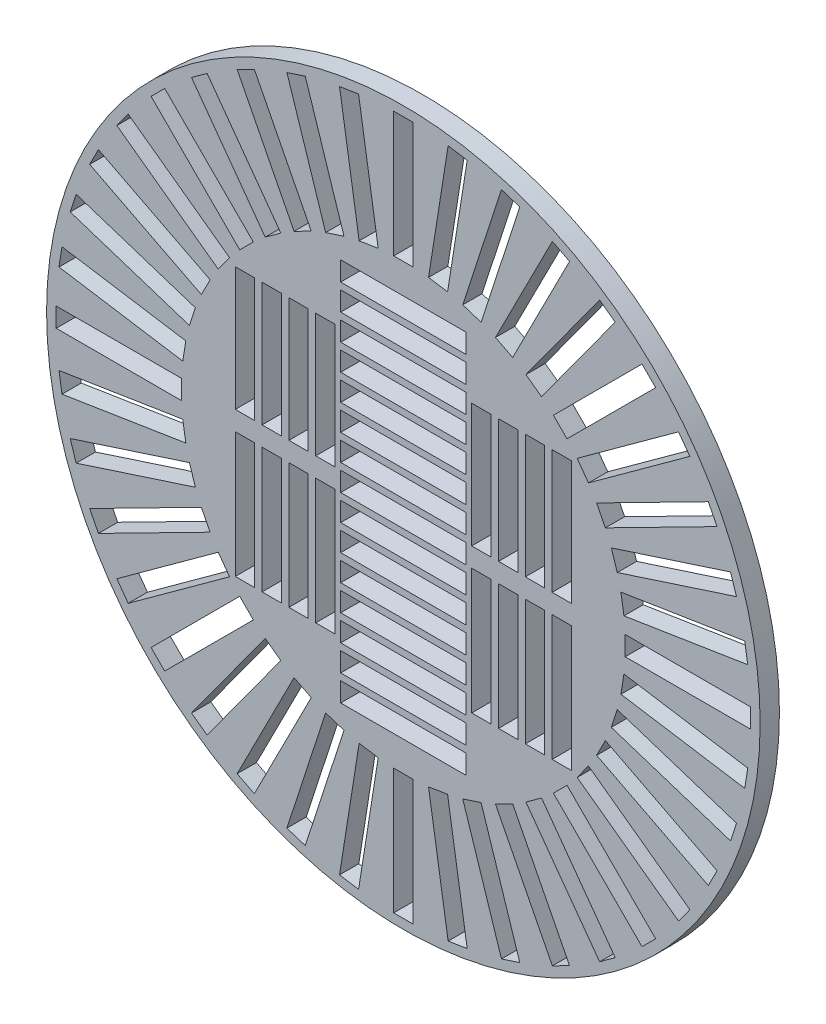
SolidWorks part; units mm, degrees
ref_plane "Front Plane" through (0, 0, 0) normal (0, 0, 1) x (1, 0, 0)
ref_plane "Top Plane" through (0, 0, 0) normal (0, 1, 0) x (1, 0, 0)
ref_plane "Right Plane" through (0, 0, 0) normal (1, 0, 0) x (0, 0, -1)
sketch "Sketch1" plane through (0, 0, 0) normal (0, 0, 1) x (1, 0, 0)
  circle A0 centre (0, 0) radius 37
  point P3 (0, 0)
  point P4 (0, 0)
  point P30 (0, 0)
  dimension "D1" = 74
extrude "Base" add sketch "Sketch1" along normal mid plane 2
sketch "Sketch Ytre ring" plane through (0, 0, 1) normal (0, 0, 1) x (1, 0, 0)
  line L0 (0, 36) -> (0, 37) construction
  line L1 (-1, 36) -> (1, 36)
  line L2 (-1, 36) -> (-1, 23)
  line L3 (-1, 23) -> (1, 23)
  line L4 (1, 36) -> (1, 23)
  circle A0 centre (0, 0) radius 37 construction
  point P4 (0, 23)
  dimension "D1" = 2
  dimension "D3" = 13
  dimension "D2" = 1
extrude "Ytre ring" cut sketch "Sketch Ytre ring" against normal blind 2
pattern_circular "CirPattern1" count 40 over 360 about axis through (0, 0, 0) along (0, 0, 1) of "Ytre ring"
sketch "Sketch3" plane through (0, 0, 1) normal (0, 0, 1) x (1, 0, 0)
  line L0 (-6.5, 3.7) -> (-6.5, 1.7)
  line L5 (-6.5, 1) -> (6.5, 1)
  line L6 (-6.5, 1) -> (-6.5, -1)
  line L7 (-6.5, -1) -> (6.5, -1)
  line L8 (6.5, 1) -> (6.5, -1)
  line L9 (-6.5, 1) -> (6.5, -1) construction
  line L10 (-6.5, -1) -> (6.5, 1) construction
  line L11 (-6.5, 3.7) -> (6.5, 3.7)
  line L12 (6.5, 3.7) -> (6.5, 1.7)
  line L13 (-6.5, 1.7) -> (6.5, 1.7)
  line L14 (-6.5, 6.4) -> (-6.5, 4.4)
  line L15 (-6.5, 6.4) -> (6.5, 6.4)
  line L16 (6.5, 6.4) -> (6.5, 4.4)
  line L17 (-6.5, 4.4) -> (6.5, 4.4)
  line L18 (-6.5, 9.1) -> (-6.5, 7.1)
  line L19 (-6.5, 9.1) -> (6.5, 9.1)
  line L20 (6.5, 9.1) -> (6.5, 7.1)
  line L21 (-6.5, 7.1) -> (6.5, 7.1)
  line L22 (-6.5, 11.8) -> (-6.5, 9.8)
  line L23 (-6.5, 11.8) -> (6.5, 11.8)
  line L24 (6.5, 11.8) -> (6.5, 9.8)
  line L25 (-6.5, 9.8) -> (6.5, 9.8)
  line L26 (-6.5, 14.5) -> (-6.5, 12.5)
  line L27 (-6.5, 14.5) -> (6.5, 14.5)
  line L28 (6.5, 14.5) -> (6.5, 12.5)
  line L29 (-6.5, 12.5) -> (6.5, 12.5)
  line L30 (-6.5, 17.2) -> (-6.5, 15.2)
  line L31 (-6.5, 17.2) -> (6.5, 17.2)
  line L32 (6.5, 17.2) -> (6.5, 15.2)
  line L33 (-6.5, 15.2) -> (6.5, 15.2)
  line L34 (-6.5, 19.9) -> (-6.5, 17.9)
  line L35 (-6.5, 19.9) -> (6.5, 19.9)
  line L36 (6.5, 19.9) -> (6.5, 17.9)
  line L37 (-6.5, 17.9) -> (6.5, 17.9)
  line L38 (-6.5, -1.7) -> (-6.5, -3.7)
  line L39 (-6.5, -1.7) -> (6.5, -1.7)
  line L40 (6.5, -1.7) -> (6.5, -3.7)
  line L41 (-6.5, -3.7) -> (6.5, -3.7)
  line L42 (-6.5, -4.4) -> (-6.5, -6.4)
  line L43 (-6.5, -4.4) -> (6.5, -4.4)
  line L44 (6.5, -4.4) -> (6.5, -6.4)
  line L45 (-6.5, -6.4) -> (6.5, -6.4)
  line L46 (-6.5, -7.1) -> (-6.5, -9.1)
  line L47 (-6.5, -7.1) -> (6.5, -7.1)
  line L48 (6.5, -7.1) -> (6.5, -9.1)
  line L49 (-6.5, -9.1) -> (6.5, -9.1)
  line L50 (-6.5, -9.8) -> (-6.5, -11.8)
  line L51 (-6.5, -9.8) -> (6.5, -9.8)
  line L52 (6.5, -9.8) -> (6.5, -11.8)
  line L53 (-6.5, -11.8) -> (6.5, -11.8)
  line L54 (-6.5, -12.5) -> (-6.5, -14.5)
  line L55 (-6.5, -12.5) -> (6.5, -12.5)
  line L56 (6.5, -12.5) -> (6.5, -14.5)
  line L57 (-6.5, -14.5) -> (6.5, -14.5)
  line L58 (-6.5, -15.2) -> (-6.5, -17.2)
  line L59 (-6.5, -15.2) -> (6.5, -15.2)
  line L60 (6.5, -15.2) -> (6.5, -17.2)
  line L61 (-6.5, -17.2) -> (6.5, -17.2)
  line L62 (-6.5, -17.9) -> (-6.5, -19.9)
  line L63 (-6.5, -17.9) -> (6.5, -17.9)
  line L64 (6.5, -17.9) -> (6.5, -19.9)
  line L65 (-6.5, -19.9) -> (6.5, -19.9)
  line L66 (0, 0) -> (0, 2.8459) construction
  line L67 (0, 0) -> (3.4244, 0) construction
  line L68 (-8.089, 1) -> (-8.089, -1) construction
  line L69 (-9.089, 13.8166) -> (-7.089, 13.8166)
  line L70 (-9.089, 13.8166) -> (-9.089, 1)
  line L71 (-9.089, 1) -> (-7.089, 1)
  line L72 (-7.089, 13.8166) -> (-7.089, 1)
  line L73 (-9.089, 13.8166) -> (-7.089, 1) construction
  line L74 (-9.089, 1) -> (-7.089, 13.8166) construction
  line L75 (-9.089, -1) -> (-7.089, -1)
  line L76 (-9.089, -1) -> (-9.089, -14)
  line L77 (-9.089, -14) -> (-7.089, -14)
  line L78 (-7.089, -1) -> (-7.089, -14)
  line L79 (-9.089, -1) -> (-7.089, -14) construction
  line L80 (-9.089, -14) -> (-7.089, -1) construction
  line L81 (-11.869, 13.8166) -> (-11.869, 1)
  line L82 (-11.869, 13.8166) -> (-9.869, 13.8166)
  line L83 (-9.869, 13.8166) -> (-9.869, 1)
  line L84 (-11.869, 1) -> (-9.869, 1)
  line L85 (-11.869, -1) -> (-11.869, -14)
  line L86 (-11.869, -1) -> (-9.869, -1)
  line L87 (-9.869, -1) -> (-9.869, -14)
  line L88 (-11.869, -14) -> (-9.869, -14)
  line L89 (-14.649, 13.8166) -> (-14.649, 1)
  line L90 (-14.649, 13.8166) -> (-12.649, 13.8166)
  line L91 (-12.649, 13.8166) -> (-12.649, 1)
  line L92 (-14.649, 1) -> (-12.649, 1)
  line L93 (-14.649, -1) -> (-14.649, -14)
  line L94 (-14.649, -1) -> (-12.649, -1)
  line L95 (-12.649, -1) -> (-12.649, -14)
  line L96 (-14.649, -14) -> (-12.649, -14)
  line L97 (-17.429, 13.8166) -> (-17.429, 1)
  line L98 (-17.429, 13.8166) -> (-15.429, 13.8166)
  line L99 (-15.429, 13.8166) -> (-15.429, 1)
  line L100 (-17.429, 1) -> (-15.429, 1)
  line L101 (-17.429, -1) -> (-17.429, -14)
  line L102 (-17.429, -1) -> (-15.429, -1)
  line L103 (-15.429, -1) -> (-15.429, -14)
  line L104 (-17.429, -14) -> (-15.429, -14)
  line L105 (11.869, 13.8166) -> (9.869, 13.8166)
  line L106 (9.869, 13.8166) -> (9.869, 1)
  line L107 (11.869, 1) -> (9.869, 1)
  line L108 (11.869, 13.8166) -> (11.869, 1)
  line L109 (9.089, 1) -> (7.089, 1)
  line L110 (7.089, 13.8166) -> (7.089, 1)
  line L111 (9.089, 13.8166) -> (7.089, 13.8166)
  line L112 (9.089, 13.8166) -> (9.089, 1)
  line L113 (9.089, -14) -> (7.089, -14)
  line L114 (7.089, -1) -> (7.089, -14)
  line L115 (9.089, -1) -> (7.089, -1)
  line L116 (9.089, -1) -> (9.089, -14)
  line L117 (11.869, -1) -> (9.869, -1)
  line L118 (9.869, -1) -> (9.869, -14)
  line L119 (11.869, -14) -> (9.869, -14)
  line L120 (11.869, -1) -> (11.869, -14)
  line L121 (14.649, 13.8166) -> (12.649, 13.8166)
  line L122 (12.649, 13.8166) -> (12.649, 1)
  line L123 (14.649, 1) -> (12.649, 1)
  line L124 (14.649, 13.8166) -> (14.649, 1)
  line L125 (14.649, -1) -> (12.649, -1)
  line L126 (12.649, -1) -> (12.649, -14)
  line L127 (14.649, -14) -> (12.649, -14)
  line L128 (14.649, -1) -> (14.649, -14)
  line L129 (17.429, -1) -> (15.429, -1)
  line L130 (15.429, -1) -> (15.429, -14)
  line L131 (17.429, -14) -> (15.429, -14)
  line L132 (17.429, -1) -> (17.429, -14)
  line L133 (17.429, 13.8166) -> (15.429, 13.8166)
  line L134 (15.429, 13.8166) -> (15.429, 1)
  line L135 (17.429, 1) -> (15.429, 1)
  line L136 (17.429, 13.8166) -> (17.429, 1)
  point P0 (0, 0)
  point P66 (-8.089, -7.5)
  point P68 (-8.089, 7.4083)
  point P77 (-8.089, 0)
  dimension "D1" = 2
  dimension "D2" = 13
  dimension "D5" = 2
  dimension "D6" = 13
  dimension "D7" = 2
  dimension "D8" = 12.8166
  dimension "D9" = 2
  dimension "D3" = 8
  dimension "D4" = 8
  dimension "D10" = 4
extrude "Cut-Extrude1" cut sketch "Sketch3" against normal blind 10
equation "\"Strekktest bredde\"= 13"
equation "\"Strekktest tykkelse\"= 2"
equation "\"D3@Sketch Ytre ring\" = \"Strekktest bredde\""
equation "\"D1@Sketch Ytre ring\" = \"Strekktest tykkelse\""
equation "\"D1@Sketch3\"=\"Strekktest tykkelse\""
equation "\"D2@Sketch3\"=\"Strekktest bredde\""
equation "\"D5@Sketch3\"=\"Strekktest tykkelse\""
equation "\"D6@Sketch3\"=\"Strekktest bredde\""
equation "\"D7@Sketch3\"=\"Strekktest tykkelse\""
